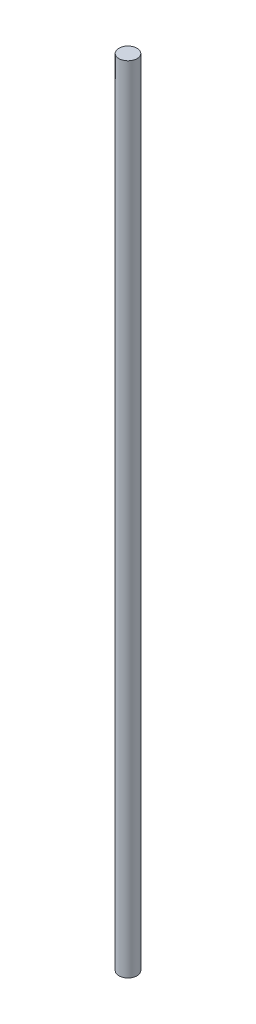
SolidWorks part; units mm, degrees
ref_plane "Front Plane" through (0, 0, 0) normal (0, 0, 1) x (1, 0, 0)
ref_plane "Top Plane" through (0, 0, 0) normal (0, 1, 0) x (1, 0, 0)
ref_plane "Right Plane" through (0, 0, 0) normal (1, 0, 0) x (0, 0, -1)
sketch "Sketch1" plane through (0, 0, 0) normal (0, 1, 0) x (1, 0, 0)
  circle A0 centre (0, 0) radius 4
extrude "Boss-Extrude1" add sketch "Sketch1" along normal blind 351
